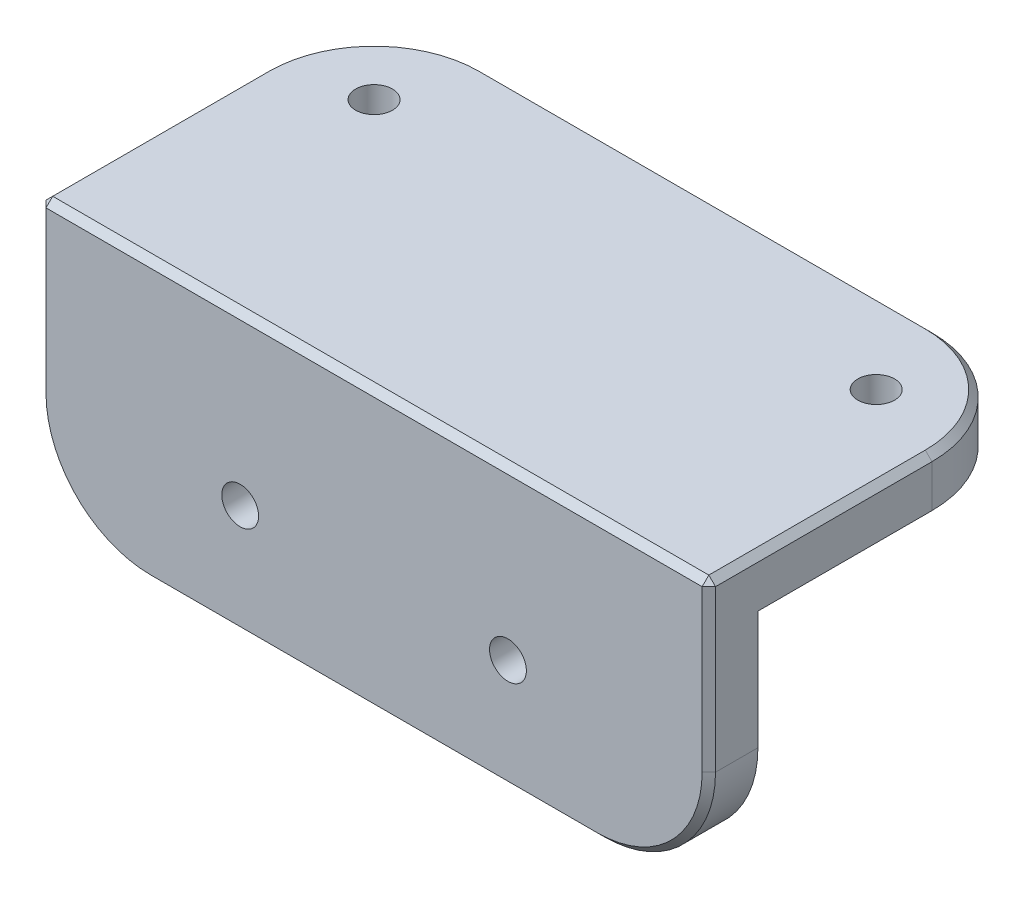
SolidWorks part; units mm, degrees
ref_plane "Front Plane" through (0, 0, 0) normal (0, 0, 1) x (1, 0, 0)
ref_plane "Top Plane" through (0, 0, 0) normal (0, 1, 0) x (1, 0, 0)
ref_plane "Right Plane" through (0, 0, 0) normal (1, 0, 0) x (0, 0, -1)
sketch "Sketch1" plane through (0, 0, 0) normal (0, 1, 0) x (1, 0, 0)
  line L1 (-30, -15) -> (30, -15)
  line L2 (-30, -15) -> (-30, 15)
  line L3 (-30, 15) -> (30, 15)
  line L4 (30, -15) -> (30, 15)
  line L5 (-30, -15) -> (30, 15) construction
  line L6 (-30, 15) -> (30, -15) construction
  point P0 (0, 0)
  dimension "D1" = 60
  dimension "D2" = 30
extrude "Boss-Extrude1" add sketch "Sketch1" along normal blind 5
sketch "Sketch2" plane through (0, 5, 0) normal (0, 1, 0) x (1, 0, 0)
  line L0 (-30, 7.5) -> (30, 7.5) construction
  line L1 (-30, 15) -> (-30, -15) construction
  line L2 (30, -15) -> (30, 15) construction
  line L3 (30, 15) -> (-30, 15) construction
  circle A0 centre (-22.5, 7.5) radius 1.65
  circle A1 centre (22.5, 7.5) radius 1.65
  dimension "D2" = 3.3
  dimension "D3" = 3.3
  dimension "D1" = 7.5
  dimension "D4" = 45
  dimension "D5" = 22.5
extrude "Cut-Extrude1" cut sketch "Sketch2" against normal through all
sketch "Sketch3" plane through (0, 0, 0) normal (0, -1, 0) x (1, 0, 0)
  line L0 (30, 15) -> (30, -15) construction
  line L1 (-30, 15) -> (30, 15)
  line L2 (-30, 15) -> (-30, 10)
  line L3 (-30, 10) -> (30, 10)
  line L4 (30, 15) -> (30, 10)
  dimension "D1" = 5
extrude "Boss-Extrude2" add sketch "Sketch3" along normal blind 20
sketch "Sketch4" plane through (0, 0, 10) normal (0, 0, -1) x (-1, 0, 0)
  line L0 (-30, -10) -> (30, -10) construction
  line L1 (-30, -20) -> (-30, 0) construction
  line L2 (30, -20) -> (30, 0) construction
  line L3 (0, 0) -> (0, -20) construction
  line L4 (30, -20) -> (-30, -20) construction
  circle A0 centre (-12, -10) radius 1.65
  circle A1 centre (12, -10) radius 1.65
  dimension "D1" = 3.3
  dimension "D2" = 12
extrude "Cut-Extrude2" cut sketch "Sketch4" against normal blind 10
fillet "Fillet1" radius 10 4 edges at (-30, 2.5, -15) (30, 2.5, -15) (-30, -20, 12.5) (30, -20, 12.5)
chamfer "Chamfer1" distance 0.6 angle 45 21 edges at (-30, 0, 2.5) (-30, -5, 10) (-27.0711, 0, -12.0711) (-27.0711, -17.0711, 10) (0, 0, -15) (0, -20, 10) (27.0711, 0, -12.0711) (27.0711, -17.0711, 10) (30, 0, 2.5) (30, -5, 10) (-30, 5, 5) (-30, -2.5, 15) (-27.0711, 5, -12.0711) (-27.0711, -17.0711, 15) (0, 5, -15) (0, -20, 15) (27.0711, 5, -12.0711) (27.0711, -17.0711, 15) (30, 5, 5) (30, -2.5, 15) (0, 5, 15)
equation "\"D5@Sketch2\"=\"D4@Sketch2\"/2"
